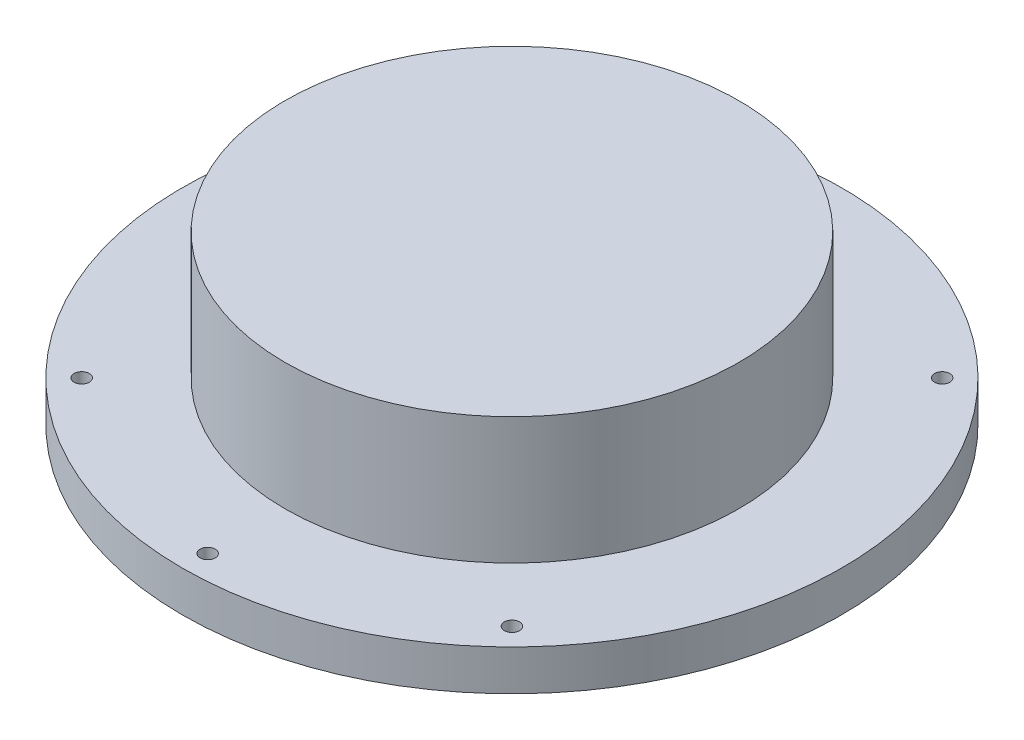
SolidWorks part; units mm, degrees
ref_plane "Front Plane" through (0, 0, 0) normal (0, 0, 1) x (1, 0, 0)
ref_plane "Top Plane" through (0, 0, 0) normal (0, 1, 0) x (1, 0, 0)
ref_plane "Right Plane" through (0, 0, 0) normal (1, 0, 0) x (0, 0, -1)
sketch "Sketch1" plane through (0, 0, 0) normal (0, 1, 0) x (1, 0, 0)
  line L0 (0, 0) -> (0, -65) construction
  circle A0 centre (0, 0) radius 65
  circle A1 centre (0, -60) radius 1.5
  circle A2 centre (-42.4264, -42.4264) radius 1.5
  circle A3 centre (-60, 0) radius 1.5 construction
  circle A4 centre (-42.4264, 42.4264) radius 1.5
  circle A5 centre (0, 60) radius 1.5
  circle A6 centre (42.4264, 42.4264) radius 1.5
  circle A7 centre (60, 0) radius 1.5 construction
  circle A8 centre (42.4264, -42.4264) radius 1.5
  point P6 (-35.4918, -37.4881)
  point P7 (0, 0)
  point P22 (0, 0)
  dimension "D2" = 3
  dimension "D3" = 130
  dimension "D4" = 5
  dimension "D1" = 8
extrude "Boss-Extrude1" add sketch "Sketch1" along normal blind 8
sketch "Sketch3" plane through (0, 8, 0) normal (0, 1, 0) x (1, 0, 0)
  circle A0 centre (0, 0) radius 44.746
extrude "Boss-Extrude2" add sketch "Sketch3" along normal blind 25
sketch "Sketch2" plane through (0, 0, 0) normal (1, 0, 0) x (0, 0, -1)
  line L0 (0, 0) -> (0, 175.4685) construction
  line L1 (-31.2067, 8) -> (-31.2067, 59.2205)
  line L6 (65, 8) -> (-65, 8) construction
  line L7 (31.2067, 8) -> (31.2067, 60.0287)
  line L8 (-31.2067, 8) -> (31.2067, 8)
  arc A0 (31.2067, 60.0287) -> (-31.2067, 59.2205) centre (-0.2252, 77.0171) ccw
  circle A1 centre (-0.2252, 77.0171) radius 7.5559
  point P5 (0, 8)
  point P12 (0, 0)
  point P13 (0, 78.0203)
  point P14 (0, 0)
  point P15 (-0.2252, 77.0171)
